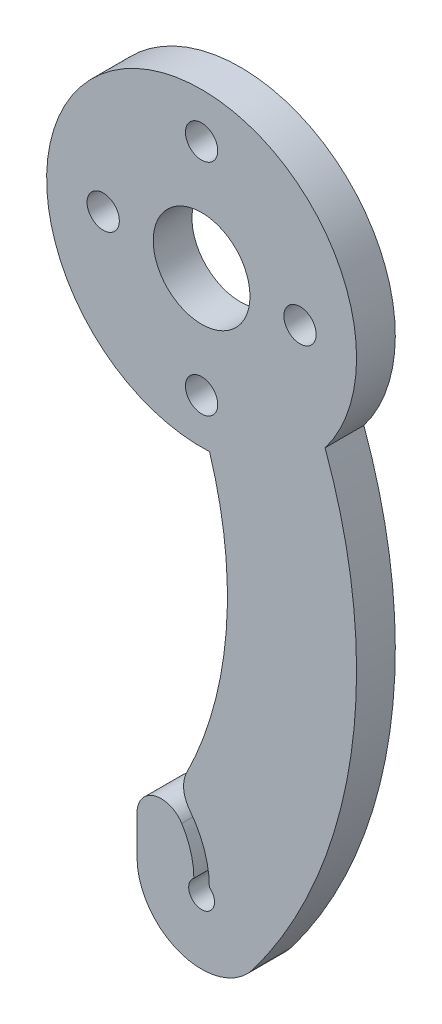
SolidWorks part; units mm, degrees
ref_plane "Front Plane" through (0, 0, 0) normal (0, 0, 1) x (1, 0, 0)
ref_plane "Top Plane" through (0, 0, 0) normal (0, 1, 0) x (1, 0, 0)
ref_plane "Right Plane" through (0, 0, 0) normal (1, 0, 0) x (0, 0, -1)
sketch "Sketch1" plane through (0, 0, 0) normal (0, 0, 1) x (1, 0, 0)
  line L0 (0, 0) -> (0, -42) construction
  line L2 (-5, -42) -> (-5, -39)
  circle A0 centre (0, 0) radius 3.7465 construction
  arc A1 (9.5624, -7.2499) -> (0.6132, -11.9843) centre (0, 0) ccw
  arc A2 (4, -45) -> (-5, -42) centre (0, -42) cw
  circle A4 centre (0, 0) radius 3.7465
  circle A6 centre (0, 8.509) radius 1.25
  circle A10 centre (-7.62, 0) radius 1.25
  circle A11 centre (0, -8.509) radius 1.25
  circle A12 centre (7.62, 0) radius 1.25
  arc A13 (-0.6, -41.2) -> (0.6, -41.2) centre (0, -42) ccw
  arc A14 (-5, -39) -> (-1.5384, -37.9885) centre (-3.1214, -39) cw
  arc A15 (-1.5384, -37.9885) -> (-0.6, -41.2) centre (-6.5645, -41.2) cw
  arc A16 (-0.9153, -36.7936) -> (-1.1557, -34.3934) centre (0.8677, -35.4029) cw
  arc A17 (-0.9153, -36.7936) -> (0.6, -41.2) centre (-6.5645, -41.2) cw
  arc A18 (0.6132, -11.9843) -> (-1.1557, -34.3934) centre (-28, -21) cw
  arc A19 (9.5624, -7.2499) -> (4, -45) centre (-28, -21) cw
  arc A20 (0, 0) -> (0, -42) centre (-28, -21) cw construction
  circle A21 centre (-7.62, 0) radius 0.7366 construction
  circle A22 centre (0, 8.509) radius 0.7366 construction
  circle A23 centre (7.62, 0) radius 0.7366 construction
  circle A24 centre (0, -8.509) radius 0.7366 construction
  dimension "D3" = 2
  dimension "D7" = 1.2
  dimension "D1" = 5
  dimension "D8" = 10
  dimension "D5" = 35
  dimension "D9" = 5
  dimension "D11" = 2.5
  dimension "D12" = 12
  dimension "D2" = 42
  dimension "D4" = 1.2
  dimension "D6" = 3
  dimension "D10" = 6
extrude "Boss-Extrude1" add sketch "Sketch1" along normal blind 3
